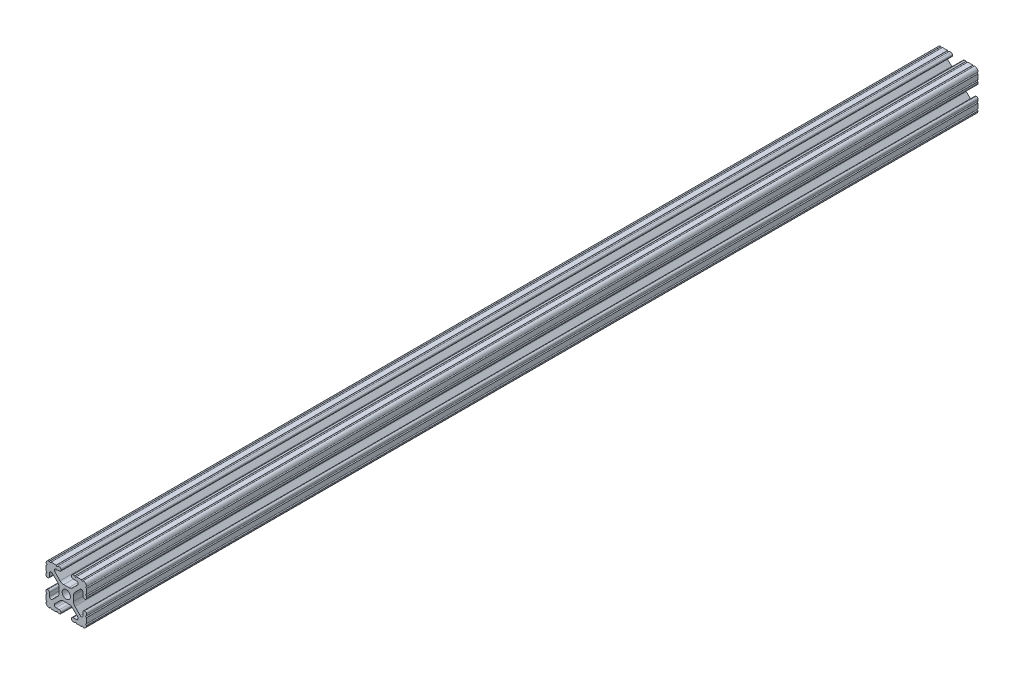
SolidWorks part; units mm, degrees
ref_plane "Front Plane" through (0, 0, 0) normal (0, 0, 1) x (1, 0, 0)
ref_plane "Top Plane" through (0, 0, 0) normal (0, 1, 0) x (1, 0, 0)
ref_plane "Right Plane" through (0, 0, 0) normal (1, 0, 0) x (0, 0, -1)
sketch "Sketch1" plane through (0, 0, 0) normal (0, 0, 1) x (1, 0, 0)
  line L0 (-7.207, 8.7244) -> (-3.8983, 5.4232)
  line L1 (-4.2875, 10.4902) -> (-6.4768, 10.4902)
  line L2 (-3.2385, 11.651) -> (-3.2385, 11.5392)
  line L3 (-5.3171, 12.7) -> (-4.2875, 12.7)
  line L4 (0, 13.4005) -> (0, -14.8534) construction
  line L5 (12.7, 0) -> (-13.9989, 0) construction
  line L6 (-9.5504, 12.7) -> (-6.3331, 12.7)
  line L7 (-12.7, 6.3331) -> (-12.7, 9.5504)
  line L8 (-12.7, 4.2875) -> (-12.7, 5.3171)
  line L9 (-11.5392, 3.2385) -> (-11.651, 3.2385)
  line L10 (-10.4902, 6.4021) -> (-10.4902, 4.2875)
  line L11 (-5.441, 3.8408) -> (-8.7371, 7.1294)
  line L12 (-4.5085, -1.5932) -> (-4.5085, 1.5932)
  line L13 (-1.7093, -4.4958) -> (1.7093, -4.4958)
  line L14 (3.9523, -5.4237) -> (7.1797, -8.6452)
  line L15 (6.4164, -10.4902) -> (4.2875, -10.4902)
  line L16 (3.2385, -11.5392) -> (3.2385, -11.651)
  line L17 (4.2875, -12.7) -> (5.3171, -12.7)
  line L18 (6.3331, -12.7) -> (9.5504, -12.7)
  line L19 (12.7, -9.5504) -> (12.7, -6.3331)
  line L20 (12.7, -5.3171) -> (12.7, -4.2875)
  line L21 (11.651, -3.2385) -> (11.5392, -3.2385)
  line L22 (10.4902, -4.2875) -> (10.4902, -6.4021)
  line L23 (8.7371, -7.1294) -> (5.441, -3.8408)
  line L24 (4.5085, -1.5932) -> (4.5085, 1.5932)
  line L25 (5.441, 3.8408) -> (8.7371, 7.1294)
  line L26 (10.4902, 6.4021) -> (10.4902, 4.2875)
  line L27 (11.5392, 3.2385) -> (11.651, 3.2385)
  line L28 (12.7, 4.2875) -> (12.7, 5.3171)
  line L29 (12.7, 6.3331) -> (12.7, 9.5504)
  line L30 (9.5504, 12.7) -> (6.3331, 12.7)
  line L31 (5.3171, 12.7) -> (4.2875, 12.7)
  line L32 (3.2385, 11.651) -> (3.2385, 11.5392)
  line L33 (4.2875, 10.4902) -> (6.4768, 10.4902)
  line L34 (7.207, 8.7244) -> (3.8983, 5.4232)
  line L35 (1.6558, 4.4958) -> (-1.6558, 4.4958)
  line L36 (-8.7371, -7.1294) -> (-5.441, -3.8408)
  line L37 (-10.4902, -4.2875) -> (-10.4902, -6.4021)
  line L38 (-11.651, -3.2385) -> (-11.5392, -3.2385)
  line L39 (-12.7, -5.3171) -> (-12.7, -4.2875)
  line L40 (-12.7, -9.5504) -> (-12.7, -6.3331)
  line L41 (-6.3331, -12.7) -> (-9.5504, -12.7)
  line L42 (-4.2875, -12.7) -> (-5.3171, -12.7)
  line L43 (-3.2385, -11.5392) -> (-3.2385, -11.651)
  line L44 (-6.4164, -10.4902) -> (-4.2875, -10.4902)
  line L45 (-3.9523, -5.4237) -> (-7.1797, -8.6452)
  arc A0 (-7.207, 8.7244) -> (-6.4768, 10.4902) centre (-6.4768, 9.4563) cw
  arc A1 (-3.2385, 11.5392) -> (-4.2875, 10.4902) centre (-4.2875, 11.5392) cw
  arc A2 (-4.2875, 12.7) -> (-3.2385, 11.651) centre (-4.2875, 11.651) cw
  arc A3 (-5.3171, 12.7) -> (-6.3331, 12.7) centre (-5.8251, 12.7) cw
  arc A4 (-9.5504, 12.7) -> (-10.5664, 12.6998) centre (-10.0584, 12.7) cw
  arc A5 (-12.6998, 10.5664) -> (-10.5664, 12.6998) centre (-10.5918, 10.5918) cw
  arc A6 (-12.6998, 10.5664) -> (-12.7, 9.5504) centre (-12.7, 10.0584) cw
  arc A7 (-12.7, 6.3331) -> (-12.7, 5.3171) centre (-12.7, 5.8251) cw
  arc A8 (-11.651, 3.2385) -> (-12.7, 4.2875) centre (-11.651, 4.2875) cw
  arc A9 (-10.4902, 4.2875) -> (-11.5392, 3.2385) centre (-11.5392, 4.2875) cw
  circle A10 centre (0, 0) radius 2.6035
  arc A11 (-10.4902, 6.4021) -> (-8.7371, 7.1294) centre (-9.4628, 6.4021) cw
  arc A12 (-5.441, 3.8408) -> (-4.5085, 1.5932) centre (-7.6835, 1.5932) cw
  arc A13 (-4.5085, -1.5932) -> (-5.441, -3.8408) centre (-7.6835, -1.5932) cw
  arc A14 (-8.7371, -7.1294) -> (-10.4902, -6.4021) centre (-9.4628, -6.4021) cw
  arc A15 (-1.7093, -4.4958) -> (-3.9523, -5.4237) centre (-1.7093, -7.6708) ccw
  arc A16 (3.9523, -5.4237) -> (1.7093, -4.4958) centre (1.7093, -7.6708) ccw
  arc A17 (6.4164, -10.4902) -> (7.1797, -8.6452) centre (6.4164, -9.4098) ccw
  arc A18 (4.2875, -10.4902) -> (3.2385, -11.5392) centre (4.2875, -11.5392) ccw
  arc A19 (3.2385, -11.651) -> (4.2875, -12.7) centre (4.2875, -11.651) ccw
  arc A20 (6.3331, -12.7) -> (5.3171, -12.7) centre (5.8251, -12.7) ccw
  arc A21 (10.5664, -12.6998) -> (9.5504, -12.7) centre (10.0584, -12.7) ccw
  arc A22 (10.5664, -12.6998) -> (12.6998, -10.5664) centre (10.5918, -10.5918) ccw
  arc A23 (12.7, -9.5504) -> (12.6998, -10.5664) centre (12.7, -10.0584) ccw
  arc A24 (12.7, -5.3171) -> (12.7, -6.3331) centre (12.7, -5.8251) ccw
  arc A25 (12.7, -4.2875) -> (11.651, -3.2385) centre (11.651, -4.2875) ccw
  arc A26 (11.5392, -3.2385) -> (10.4902, -4.2875) centre (11.5392, -4.2875) ccw
  arc A27 (8.7371, -7.1294) -> (10.4902, -6.4021) centre (9.4628, -6.4021) ccw
  arc A28 (4.5085, -1.5932) -> (5.441, -3.8408) centre (7.6835, -1.5932) ccw
  arc A29 (5.441, 3.8408) -> (4.5085, 1.5932) centre (7.6835, 1.5932) ccw
  arc A30 (10.4902, 6.4021) -> (8.7371, 7.1294) centre (9.4628, 6.4021) ccw
  arc A31 (10.4902, 4.2875) -> (11.5392, 3.2385) centre (11.5392, 4.2875) ccw
  arc A32 (11.651, 3.2385) -> (12.7, 4.2875) centre (11.651, 4.2875) ccw
  arc A33 (12.7, 6.3331) -> (12.7, 5.3171) centre (12.7, 5.8251) ccw
  arc A34 (12.6998, 10.5664) -> (12.7, 9.5504) centre (12.7, 10.0584) ccw
  arc A35 (12.6998, 10.5664) -> (10.5664, 12.6998) centre (10.5918, 10.5918) ccw
  arc A36 (9.5504, 12.7) -> (10.5664, 12.6998) centre (10.0584, 12.7) ccw
  arc A37 (5.3171, 12.7) -> (6.3331, 12.7) centre (5.8251, 12.7) ccw
  arc A38 (4.2875, 12.7) -> (3.2385, 11.651) centre (4.2875, 11.651) ccw
  arc A39 (3.2385, 11.5392) -> (4.2875, 10.4902) centre (4.2875, 11.5392) ccw
  arc A40 (7.207, 8.7244) -> (6.4768, 10.4902) centre (6.4768, 9.4563) ccw
  arc A41 (1.6558, 4.4958) -> (3.8983, 5.4232) centre (1.6558, 7.6708) ccw
  arc A42 (-1.6558, 4.4958) -> (-3.8983, 5.4232) centre (-1.6558, 7.6708) cw
  arc A43 (-11.5392, -3.2385) -> (-10.4902, -4.2875) centre (-11.5392, -4.2875) cw
  arc A44 (-12.7, -4.2875) -> (-11.651, -3.2385) centre (-11.651, -4.2875) cw
  arc A45 (-12.7, -5.3171) -> (-12.7, -6.3331) centre (-12.7, -5.8251) cw
  arc A46 (-12.7, -9.5504) -> (-12.6998, -10.5664) centre (-12.7, -10.0584) cw
  arc A47 (-10.5664, -12.6998) -> (-12.6998, -10.5664) centre (-10.5918, -10.5918) cw
  arc A48 (-10.5664, -12.6998) -> (-9.5504, -12.7) centre (-10.0584, -12.7) cw
  arc A49 (-6.3331, -12.7) -> (-5.3171, -12.7) centre (-5.8251, -12.7) cw
  arc A50 (-3.2385, -11.651) -> (-4.2875, -12.7) centre (-4.2875, -11.651) cw
  arc A51 (-4.2875, -10.4902) -> (-3.2385, -11.5392) centre (-4.2875, -11.5392) cw
  arc A52 (-6.4164, -10.4902) -> (-7.1797, -8.6452) centre (-6.4164, -9.4098) cw
  dimension "D1" = 5.207
  dimension "D9" = 14.859
  dimension "D2" = 25.4
  dimension "D3" = 12.7
  dimension "D4" = 6.477
  dimension "D5" = 8.2042
  dimension "D6" = 9.017
  dimension "D8" = 2.2098
  dimension "D10" = 2.2098
extrude "Extrude1" add sketch "Sketch1" against normal blind 558.8
